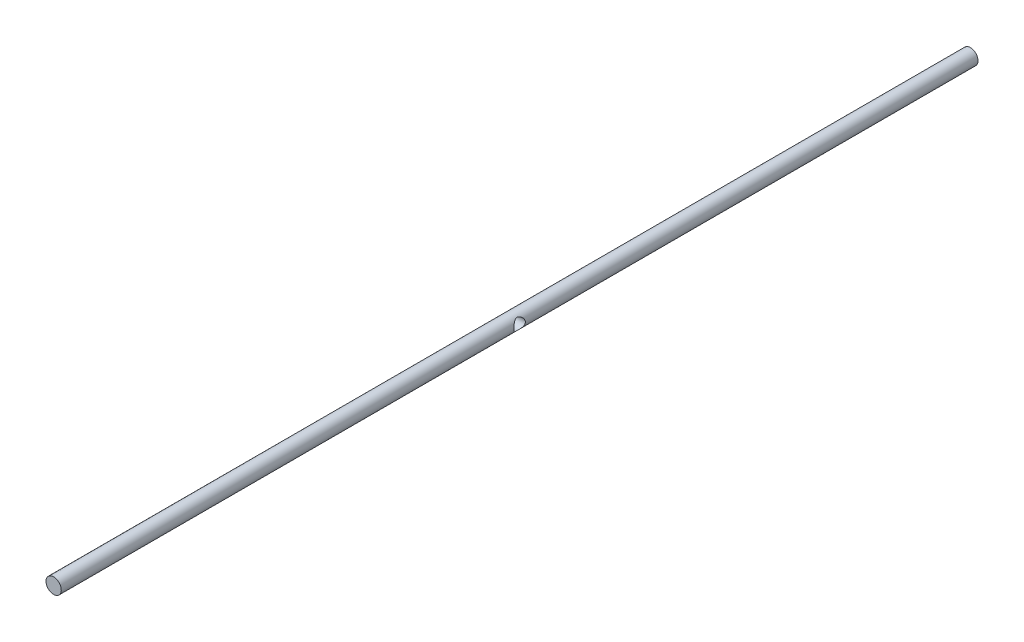
SolidWorks part; units mm, degrees
ref_plane "Front Plane" through (0, 0, 0) normal (0, 0, 1) x (1, 0, 0)
ref_plane "Top Plane" through (0, 0, 0) normal (0, 1, 0) x (1, 0, 0)
ref_plane "Right Plane" through (0, 0, 0) normal (1, 0, 0) x (0, 0, -1)
sketch "Sketch1" plane through (0, 0, 0) normal (0, 0, 1) x (1, 0, 0)
  circle A0 centre (0, 0) radius 6.35
  dimension "D1" = 12.7
extrude "Boss-Extrude1" add sketch "Sketch1" along normal mid plane 762
sketch "Sketch2" plane through (0, 0, 0) normal (0, 1, 0) x (1, 0, 0)
  line L0 (-6.35, 381) -> (-6.35, 431.0893) construction
  line L1 (-6.35, 381) -> (-6.35, -381) construction
sketch "Sketch4" plane through (0, 0, 0) normal (1, 0, 0) x (0, 0, -1)
  line L0 (-381, 0) -> (381, 0) construction
  line L3 (381, -6.35) -> (381, 6.35) construction
  circle A0 centre (0, 0) radius 4.7625
  dimension "D1" = 9.525
  dimension "D2" = 381
extrude "Cut-Extrude1" cut sketch "Sketch4" against normal through all both and the other way through all
